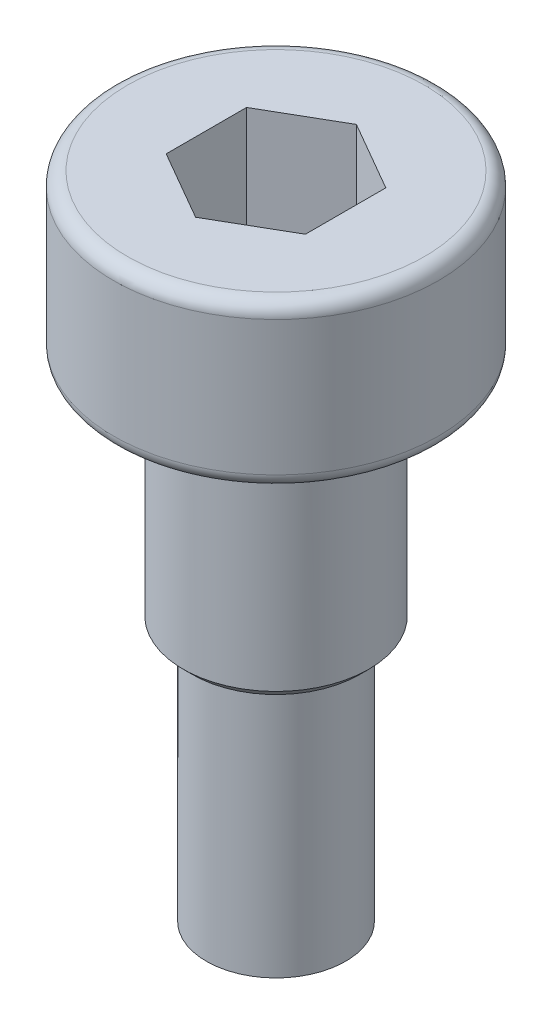
SolidWorks part; units mm, degrees
ref_plane "前视基准面" through (0, 0, 0) normal (0, 0, 1) x (1, 0, 0)
ref_plane "上视基准面" through (0, 0, 0) normal (0, 1, 0) x (1, 0, 0)
ref_plane "右视基准面" through (0, 0, 0) normal (1, 0, 0) x (0, 0, -1)
other "Configuration Table"
sketch "草图1" plane through (0, 0, 0) normal (0, 0, 1) x (1, 0, 0)
  line L0 (0, 3.5) -> (0, -12.3937) construction
  line L1 (0, 3.5) -> (-3.5, 3.5)
  line L2 (-3.5, 3.5) -> (-3.5, 0)
  line L3 (-3.5, 0) -> (-2, 0)
  line L4 (-2, 0) -> (-2, -5)
  line L5 (-2, -5) -> (-1.5, -5)
  line L6 (-1.5, -5) -> (-1.5, -10.5)
  line L7 (-1.5, -10.5) -> (0, -10.5)
  line L8 (0, 3.5) -> (0, -10.5)
  dimension "D1" = 7
  dimension "D2" = 3.5
  dimension "D3" = 5
  dimension "D4" = 4
  dimension "D5" = 3
  dimension "D6" = 5.5
revolve "旋转1" add sketch "草图1" angle 360 about L0
cosmetic thread "装饰螺纹线1" parameters "D2"=2.459
fillet "圆角1" radius 0.3 2 edges at (-3.5, 0, 0) (-3.5, 3.5, 0)
sketch "草图2" plane through (0, 3.5, 0) normal (0, 1, 0) x (1, 0, 0)
  line L1 (1.5, -0.866) -> (1.5, 0.866)
  line L2 (1.5, 0.866) -> (0, 1.7321)
  line L3 (0, 1.7321) -> (-1.5, 0.866)
  line L4 (-1.5, 0.866) -> (-1.5, -0.866)
  line L5 (-1.5, -0.866) -> (0, -1.7321)
  line L6 (0, -1.7321) -> (1.5, -0.866)
  circle A0 centre (0, 0) radius 1.5 construction
  dimension "D1" = 3
extrude "切除-拉伸1" cut sketch "草图2" against normal blind 2.4 contours L1 L2 L3 L4 L5 L6
chamfer "倒角1" distance 0.2 angle 45 1 edges at (-2, -5, 0)
